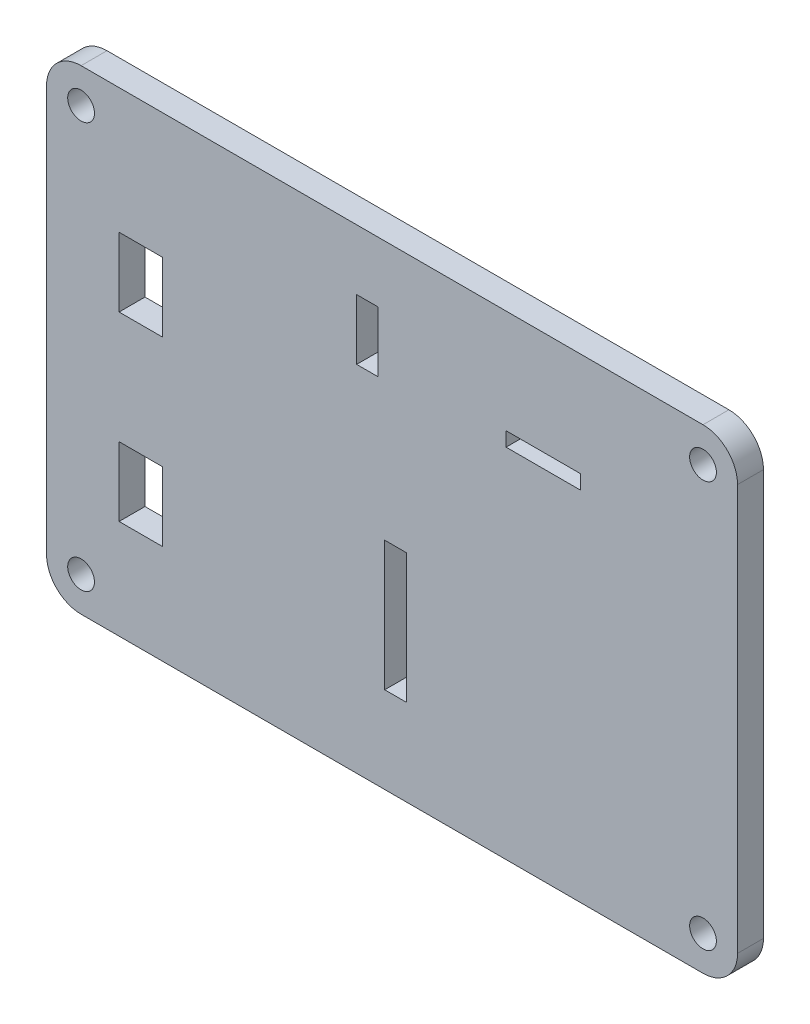
SolidWorks part; units mm, degrees
ref_plane "Plan de face" through (0, 0, 0) normal (0, 0, 1) x (1, 0, 0)
ref_plane "Plan de dessus" through (0, 0, 0) normal (0, 1, 0) x (1, 0, 0)
ref_plane "Plan de droite" through (0, 0, 0) normal (1, 0, 0) x (0, 0, -1)
sketch "Esquisse1" plane through (0, 0, 0) normal (0, 0, 1) x (1, 0, 0)
  line L0 (36, 27.5) -> (-36, 27.5)
  line L2 (40, -23.5) -> (40, 23.5)
  line L3 (-36, -27.5) -> (36, -27.5)
  line L4 (-40, 23.5) -> (-40, -23.5)
  line L6 (-26.6, -8) -> (-31.6, -8)
  line L7 (-31.6, -8) -> (-31.6, -16)
  line L8 (-31.6, -16) -> (-26.6, -16)
  line L9 (-26.6, -16) -> (-26.6, -8)
  line L10 (-26.6, 5) -> (-26.6, 13)
  line L11 (-26.6, 13) -> (-31.6, 13)
  line L12 (-31.6, 13) -> (-31.6, 5)
  line L13 (-31.6, 5) -> (-26.6, 5)
  line L14 (1.65, -17.5) -> (1.65, -2.5)
  line L15 (1.65, -2.5) -> (-0.85, -2.5)
  line L16 (-0.85, -2.5) -> (-0.85, -17.5)
  line L17 (-0.85, -17.5) -> (1.65, -17.5)
  line L18 (-1.6, 13.5) -> (-1.6, 20.5)
  line L19 (-1.6, 20.5) -> (-4.1, 20.5)
  line L20 (-4.1, 20.5) -> (-4.1, 13.5)
  line L21 (-4.1, 13.5) -> (-1.6, 13.5)
  line L22 (21.8, 15.5) -> (13.2, 15.5)
  line L23 (13.2, 15.5) -> (13.2, 13.85)
  line L24 (21.8, 13.85) -> (21.8, 15.5)
  line L25 (13.2, 13.85) -> (21.8, 13.85)
  arc A0 (-36, 27.5) -> (-40, 23.5) centre (-36, 23.5) ccw
  arc A1 (40, 23.5) -> (36, 27.5) centre (36, 23.5) ccw
  arc A2 (36, -27.5) -> (40, -23.5) centre (36, -23.5) ccw
  arc A3 (-40, -23.5) -> (-36, -27.5) centre (-36, -23.5) ccw
  circle A4 centre (-36, 23.5) radius 1.55
  circle A5 centre (-36, -23.5) radius 1.55
  circle A6 centre (36, -23.5) radius 1.55
  circle A7 centre (36, 23.5) radius 1.55
  dimension "D6" = 4
  dimension "D7" = 3.1
  dimension "D8" = 4
  dimension "D9" = 4
  dimension "D10" = 4
  dimension "D11" = 4
  dimension "D12" = 4
  dimension "D13" = 4
  dimension "D14" = 4
  dimension "D1" = 80
  dimension "D2" = 40
  dimension "D3" = 27.5
  dimension "D4" = 55
  dimension "D5" = 4
  dimension "D15" = 8
  dimension "D16" = 13
  dimension "D17" = 8
  dimension "D18" = 11.5
  dimension "D19" = 8.4
  dimension "D20" = 5
  dimension "D21" = 40.85
  dimension "D22" = 2.5
  dimension "D23" = 0.75
  dimension "D24" = 2.5
  dimension "D25" = 7
  dimension "D26" = 7
  dimension "D27" = 16
  dimension "D28" = 15
  dimension "D29" = 12
  dimension "D30" = 1.65
  dimension "D31" = 8.6
  dimension "D32" = 18.2
extrude "Boss.-Extru.1" add sketch "Esquisse1" along normal blind 3
